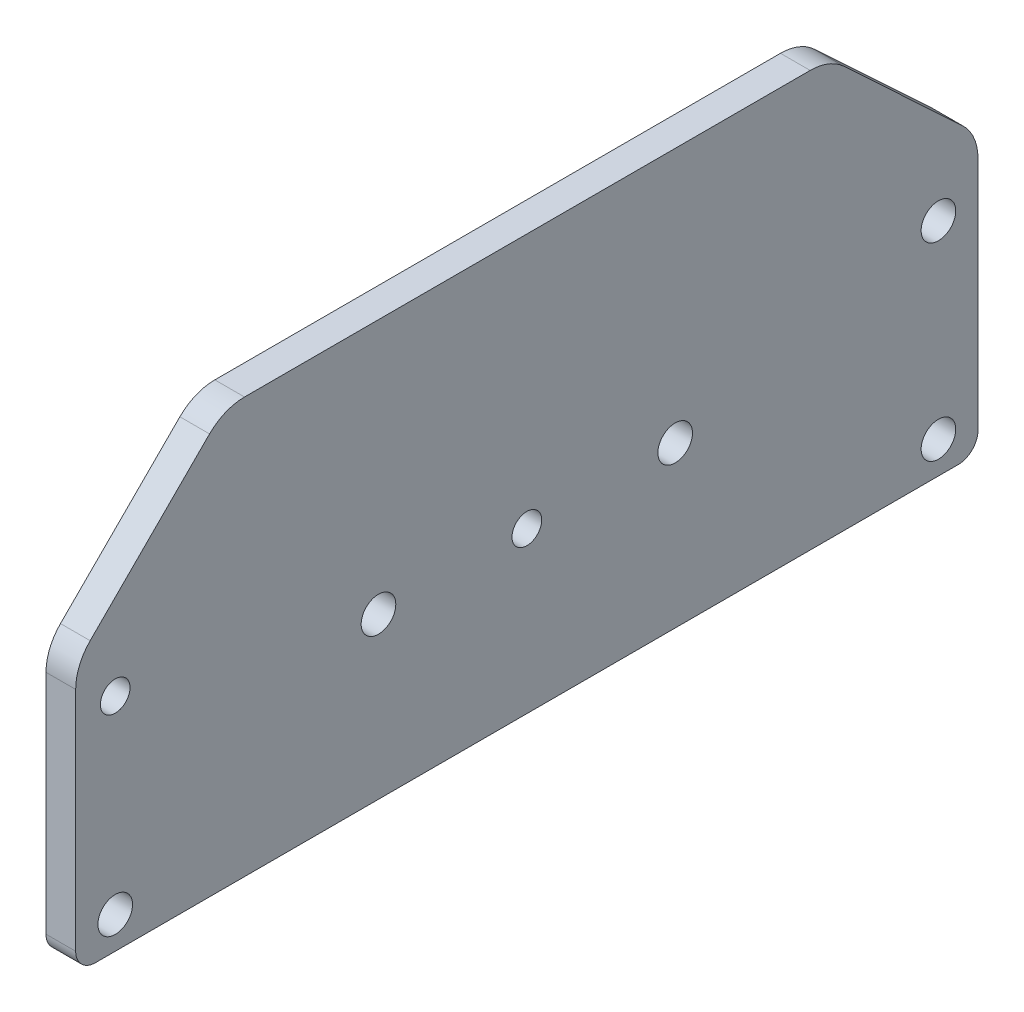
SolidWorks part; units mm, degrees
ref_plane "Front Plane" through (0, 0, 0) normal (0, 0, 1) x (1, 0, 0)
ref_plane "Top Plane" through (0, 0, 0) normal (0, 1, 0) x (1, 0, 0)
ref_plane "Right Plane" through (0, 0, 0) normal (1, 0, 0) x (0, 0, -1)
sketch "Sketch1" plane through (0, 0, 0) normal (1, 0, 0) x (0, 0, -1)
  line L0 (0, 20) -> (0, 29.8738)
  line L1 (0, 29.8738) -> (0, 249.2893)
  line L4 (912.32, 258.2724) -> (912.32, 20)
  line L5 (892.32, 0) -> (20, 0)
  line L6 (40, 223.5077) -> (40, 32.2453)
  line L7 (40, 32.2453) -> (306.16, 162.0577)
  line L8 (306.16, 162.0577) -> (40, 223.5077)
  line L9 (456.16, 0) -> (456.16, 222.215)
  line L10 (872.32, 223.5077) -> (872.32, 32.2453)
  line L11 (872.32, 32.2453) -> (606.16, 162.0577)
  line L12 (606.16, 162.0577) -> (872.32, 223.5077)
  line L13 (14.6447, 284.6447) -> (135.3553, 405.3553)
  line L14 (170.7107, 420) -> (742.6118, 420)
  line L15 (776.7278, 406.5528) -> (896.4359, 294.8251)
  line L25 (806.6161, 64.2906) -> (806.6161, 32.2453)
  line L28 (183.3013, 31.8353) -> (183.3013, 32.2453)
  line L30 (213.3013, 31.8353) -> (213.3013, 32.0058)
  line L32 (243.3417, 31.9099) -> (243.3417, 31.9596)
  line L34 (273.3417, 31.9099) -> (273.3417, 31.9134)
  line L44 (715.044, 31.1882) -> (715.044, 31.2343)
  line L48 (795.2402, 31.0649) -> (795.2402, 31.111)
  line L56 (729.0187, 32.2453) -> (717.8487, 32.2453)
  line L64 (729.0187, 31.8353) -> (729.0187, 32.2453)
  circle A0 centre (40, 223.5077) radius 15
  circle A1 centre (306.16, 162.0577) radius 17.5
  circle A2 centre (40, 32.2453) radius 17.5
  circle A3 centre (606.16, 162.0577) radius 17.5
  circle A4 centre (872.32, 223.5077) radius 17.5
  circle A5 centre (872.32, 32.2453) radius 17.5
  arc A6 (896.4359, 294.8251) -> (912.32, 258.2724) centre (862.32, 258.2724) cw
  arc A7 (742.6118, 420) -> (776.7278, 406.5528) centre (742.6118, 370) cw
  arc A8 (135.3553, 405.3553) -> (170.7107, 420) centre (170.7107, 370) cw
  arc A9 (0, 249.2893) -> (14.6447, 284.6447) centre (50, 249.2893) cw
  arc A10 (912.32, 20) -> (892.32, 0) centre (892.32, 20) cw
  arc A11 (0, 20) -> (20, 0) centre (20, 20) ccw
  circle A12 centre (456.16, 162.0577) radius 15
  point P63 (912.32, 280)
  point P66 (762.32, 420)
  point P69 (150, 420)
  point P72 (0, 270)
  point P75 (912.32, 0)
  point P78 (0, 0)
  dimension "D8" = 150
  dimension "D14" = 30
  dimension "D7" = 150
  dimension "D11" = 50
  dimension "D24" = 20
  dimension "D25" = 912.32
  dimension "D1" = 40
  dimension "D2" = 266.16
  dimension "D3" = 39
  dimension "D4" = 61.45
  dimension "D5" = 191.2624
  dimension "D6" = 129.8124
  dimension "D9" = 150
  dimension "D10" = 280
  dimension "D12" = 270
  dimension "D13" = 135
  dimension "D23" = 136.975
extrude "Boss-Extrude1" add sketch "Sketch1" along normal blind 30
